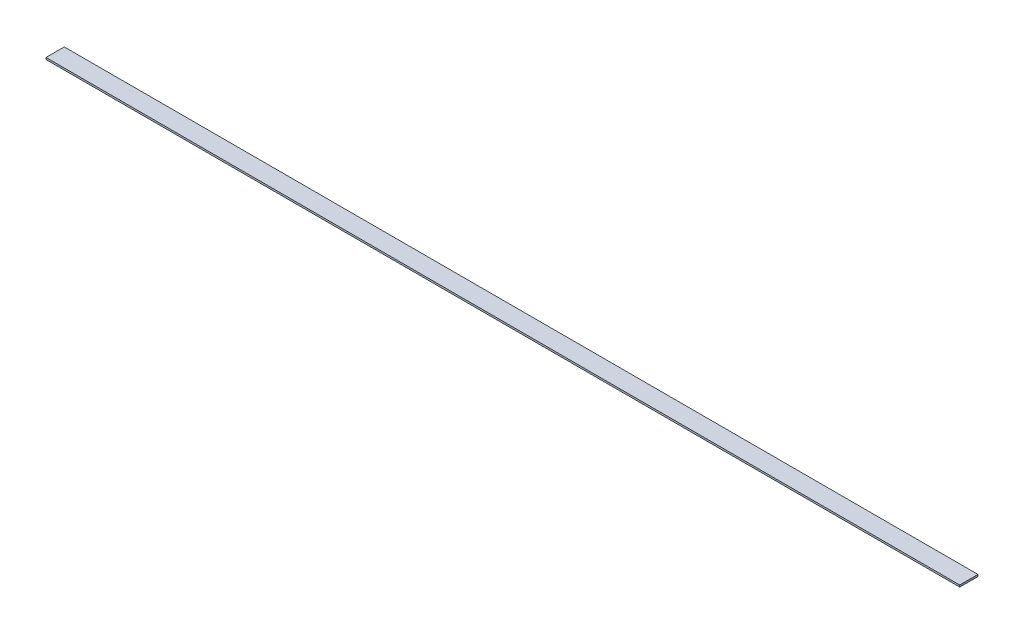
SolidWorks part; units mm, degrees
ref_plane "Front Plane" through (0, 0, 0) normal (0, 0, 1) x (1, 0, 0)
ref_plane "Top Plane" through (0, 0, 0) normal (0, 1, 0) x (1, 0, 0)
ref_plane "Right Plane" through (0, 0, 0) normal (1, 0, 0) x (0, 0, -1)
sketch "Sketch1" plane through (0, 0, 0) normal (0, 0, 1) x (1, 0, 0)
  line L1 (0, 0) -> (50000, 0)
  line L2 (0, 0) -> (0, 100)
  line L3 (0, 100) -> (50000, 100)
  line L4 (50000, 0) -> (50000, 100)
  dimension "D1" = 100
  dimension "D2" = 50000
extrude "Boss-Extrude1" add sketch "Sketch1" along normal blind 1000
